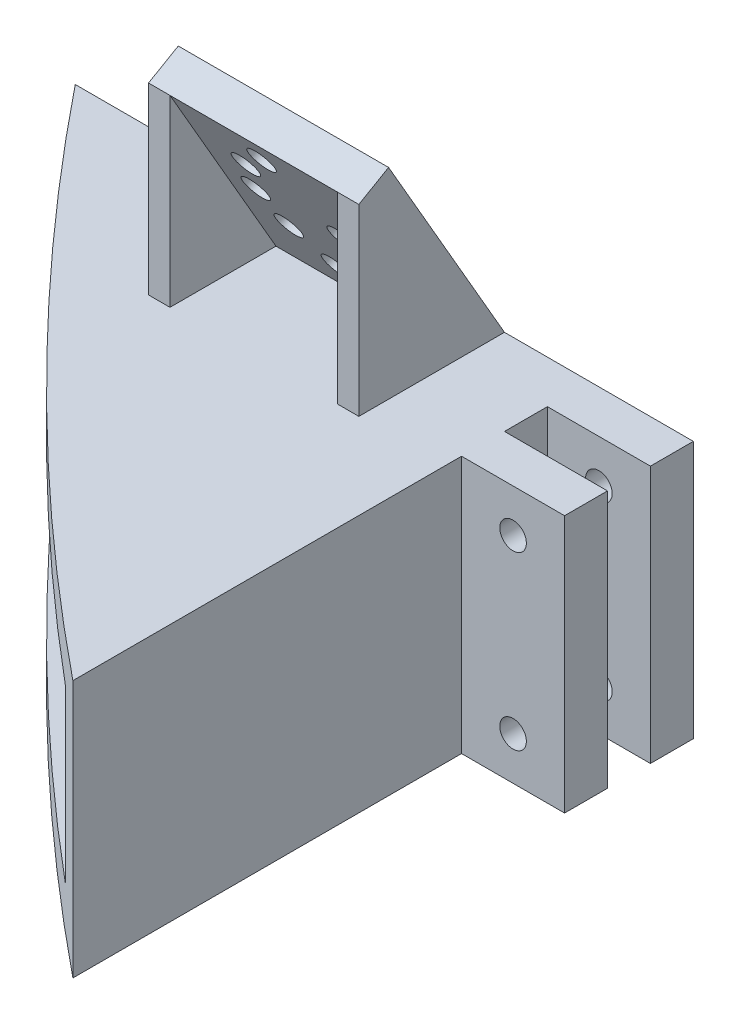
SolidWorks part; units mm, degrees
ref_plane "前视基准面" through (0, 0, 0) normal (0, 0, 1) x (1, 0, 0)
ref_plane "上视基准面" through (0, 0, 0) normal (0, 1, 0) x (1, 0, 0)
ref_plane "右视基准面" through (0, 0, 0) normal (1, 0, 0) x (0, 0, -1)
sketch "草图1" plane through (0, 0, 0) normal (0, 1, 0) x (1, 0, 0)
  line L0 (0, 0) -> (-70, 0)
  line L2 (0, 0) -> (0, -5)
  line L3 (0, -5) -> (-10, -5)
  line L4 (-10, -5) -> (-10, -10)
  line L5 (-10, -10) -> (0, -10)
  line L6 (0, -10) -> (0, -15)
  line L7 (0, -15) -> (-10, -15)
  line L8 (-10, -15) -> (-10, -60.2761)
  arc A0 (-70, 0) -> (-10, -60.2761) centre (241.8847, 250.4554) ccw
  dimension "D3" = 400
  dimension "D1" = 70
  dimension "D2" = 61.1
  dimension "D4" = 5
  dimension "D5" = 5
  dimension "D6" = 5
  dimension "D7" = 10
extrude "凸台-拉伸1" add sketch "草图1" along normal blind 30
sketch "草图2" plane through (0, 0, 0) normal (0, 0, -1) x (-1, 0, 0)
  line L0 (0, 15) -> (23.3117, 15) construction
  line L1 (0, 30) -> (0, 0) construction
  line L2 (0, 30) -> (70, 30) construction
  circle A0 centre (4, 25) radius 1.55
  circle A1 centre (4, 5) radius 1.55
  dimension "D1" = 3.1
  dimension "D2" = 4
  dimension "D3" = 5
extrude "切除-拉伸1" cut sketch "草图2" against normal through all both and the other way through all
ref_plane "基准面11" through (0, 30, 0) normal (0, 1, 0) x (1, 0, 0)
sketch "草图6" plane through (0, 30, 0) normal (0, 1, 0) x (1, 0, 0)
  line L4 (-15, -15) -> (-15, -5)
  line L5 (-59.3918, -5) -> (-65.918, -5)
  line L6 (-15, -49.6033) -> (-15, -15)
  line L7 (0, -5) -> (-59.3918, -5)
  line L8 (-15, -49.6033) -> (-15, -15)
  line L9 (-15, -5) -> (-59.3918, -5)
  line L10 (-15, -49.6033) -> (-15, -56.1555)
  arc A2 (-70, 0) -> (-10, -60.2761) centre (241.8847, 250.4554) ccw construction
  arc A3 (-59.3918, -5) -> (-15, -49.6033) centre (241.8847, 250.4554) ccw
  arc A7 (-70, 0) -> (-10, -60.2761) centre (241.8847, 250.4554) ccw
  arc A8 (-65.918, -5) -> (-15, -56.1555) centre (241.8847, 250.4554) ccw
  dimension "D2" = 0
  dimension "D1" = 5
ref_plane "基准面15" through (0, 15, 0) normal (0, 1, 0) x (1, 0, 0)
sketch "草图9" plane through (0, 15, 0) normal (0, 1, 0) x (1, 0, 0)
  line L10 (-65.918, -5) -> (-59.3918, -5)
  line L11 (-15, -49.6033) -> (-15, -56.1555)
  line L12 (-15, -49.6033) -> (-15, -15)
  line L13 (0, -5) -> (-59.3918, -5)
  line L14 (-15, -49.6033) -> (-15, -15)
  line L15 (-15, -5) -> (-59.3918, -5)
  line L16 (-15, -15) -> (-15, -5)
  arc A2 (-59.3918, -5) -> (-15, -49.6033) centre (241.8847, 250.4554) ccw
  arc A5 (-65.918, -5) -> (-15, -56.1555) centre (241.8847, 250.4554) ccw
  arc A6 (-65.918, -5) -> (-15, -56.1555) centre (241.8847, 250.4554) ccw
  dimension "D2" = 0
  dimension "D1" = 5
extrude "切除-拉伸6" cut sketch "草图9" against normal mid plane 20
sketch "草图11" plane through (0, 15, 0) normal (0, 1, 0) x (1, 0, 0)
  line L0 (-15, -5) -> (-23, -5)
  line L1 (-15, -5) -> (-59.3918, -5) construction
  line L2 (-15, -5) -> (-15, -10)
  line L3 (-15, -15) -> (-15, -5) construction
  line L4 (-15, -10) -> (-23, -5)
  dimension "D1" = 8
  dimension "D2" = 5
extrude "凸台-拉伸3" add sketch "草图11" along normal mid plane 25
ref_plane "基准面16" through (0, 0, 0) normal (0, 0, -1) x (-1, 0, 0)
sketch "草图12" plane through (0, 0, 0) normal (1, 0, 0) x (0, 0, -1)
  line L1 (-15, 30) -> (-10, 30)
  line L2 (-15, 30) -> (-15, 0)
  line L3 (-15, 0) -> (-10, 0)
  line L4 (-10, 30) -> (-10, 0)
  line L5 (-5, 0) -> (0, 0)
  line L6 (-5, 0) -> (-5, 30)
  line L7 (-5, 30) -> (0, 30)
  line L8 (0, 0) -> (0, 30)
extrude "凸台-拉伸4" add sketch "草图12" along normal blind 2
ref_plane "基准面17" through (0, 7.5, -12.9904) normal (0, 0.5, -0.866) x (-1, 0, 0)
sketch "草图14" plane through (0, 7.5, -12.9904) normal (0, 0.5, -0.866) x (-1, 0, 0)
  line L0 (-2, 25.9808) -> (70, 25.9808) construction
  line L1 (20, 25.9808) -> (42, 25.9808)
  line L2 (20, 25.9808) -> (20, 52.9808)
  line L3 (20, 52.9808) -> (42, 52.9808)
  line L4 (42, 25.9808) -> (42, 52.9808)
  line L5 (10, 30.9808) -> (10, 28.4808) construction
  line L6 (36.6603, 45.9808) -> (28, 40.9808) construction
  line L7 (28, 40.9808) -> (33, 49.641) construction
  line L8 (28, 40.9808) -> (38, 40.9808) construction
  line L9 (28, 40.9808) -> (36.6603, 35.9808) construction
  line L10 (28, 40.9808) -> (33, 32.3205) construction
  circle A0 centre (28, 40.9808) radius 1.55
  circle A3 centre (28, 40.9808) radius 10 construction
  circle A4 centre (33, 49.641) radius 1.55
  circle A5 centre (36.6603, 45.9808) radius 1.55
  circle A6 centre (38, 40.9808) radius 1.55
  circle A7 centre (36.6603, 35.9808) radius 1.55
  circle A8 centre (33, 32.3205) radius 1.55
  dimension "D2" = 8
  dimension "D4" = 60
  dimension "D8" = 3.1
  dimension "D9" = 20
  dimension "D1" = 10
  dimension "D3" = 12
  dimension "D5" = 30
  dimension "D6" = 30
  dimension "D7" = 30
extrude "凸台-拉伸5" add sketch "草图14" against normal blind 4
sketch "草图18" plane through (-20, 0, 0) normal (1, 0, 0) x (0, 0, -1)
  line L0 (-16.9641, 51.3827) -> (-4.6188, 30)
  line L1 (-16.9641, 51.3827) -> (-16.9641, 30)
  line L2 (-60.2761, 30) -> (-15, 30) construction
  line L3 (-16.9641, 30) -> (-4.6188, 30)
extrude "凸台-拉伸8" add sketch "草图18" against normal blind 2.5
sketch "草图19" plane through (-42, 0, 0) normal (-1, 0, 0) x (0, 0, 1)
  line L0 (0, 30) -> (13.5, 53.3827)
  line L1 (13.5, 53.3827) -> (16.9641, 51.3827)
  line L2 (16.9641, 51.3827) -> (13.5, 53.3827) construction
  line L3 (16.9641, 51.3827) -> (16.9641, 30)
  line L4 (16.9641, 30) -> (0, 30)
extrude "凸台-拉伸9" add sketch "草图19" along normal blind 2.5
